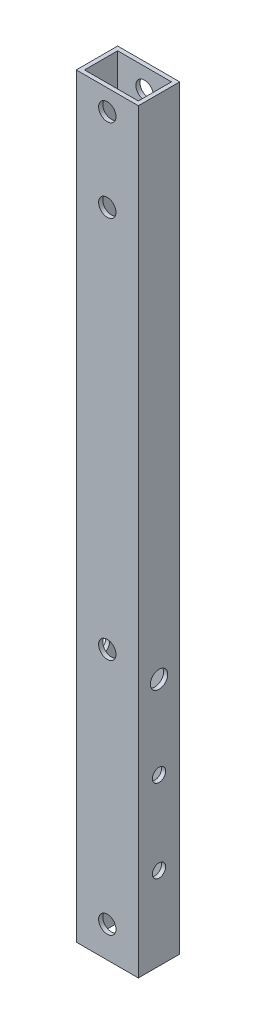
SolidWorks part; units mm, degrees
material "5052-H34"
ref_plane "正面" through (0, 0, 0) normal (0, 0, 1) x (1, 0, 0)
ref_plane "平面" through (0, 0, 0) normal (0, 1, 0) x (1, 0, 0)
ref_plane "右側面" through (0, 0, 0) normal (1, 0, 0) x (0, 0, -1)
sketch "ｽｹｯﾁ1" plane through (0, 0, 0) normal (0, 1, 0) x (1, 0, 0)
  line L1 (-7.5, 5) -> (7.5, 5)
  line L2 (-7.5, 5) -> (-7.5, -5)
  line L3 (-7.5, -5) -> (7.5, -5)
  line L4 (7.5, 5) -> (7.5, -5)
  line L5 (-7.5, 5) -> (7.5, -5) construction
  line L6 (-7.5, -5) -> (7.5, 5) construction
  point P0 (0, 0)
  dimension "D1" = 15
  dimension "D2" = 10
extrude "押し出し-薄板1" add sketch "ｽｹｯﾁ1" along normal blind 182.5 thin
sketch "ｽｹｯﾁ2" plane through (0, 0, 5) normal (0, 0, 1) x (1, 0, 0)
  line L0 (0, 182.5) -> (0, 0) construction
  line L1 (-7.5, 182.5) -> (7.5, 182.5) construction
  line L2 (0, 7.5) -> (-7.5, 7.5) construction
  line L4 (-7.5, 182.5) -> (-7.5, 0) construction
  line L5 (-7.5, 0) -> (7.5, 0) construction
  circle A2 centre (0, 7.5) radius 2.1
  circle A3 centre (0, 65) radius 2.1
  circle A4 centre (0, 157.5) radius 2.1
  circle A5 centre (0, 177.5) radius 2.1
  dimension "D1" = 4.2
  dimension "D3" = 57.5
  dimension "D2" = 7.5
  dimension "D4" = 5
  dimension "D5" = 20
extrude "ｶｯﾄ - 押し出し1" cut sketch "ｽｹｯﾁ2" against normal through all
sketch "ｽｹｯﾁ3" plane through (7.5, 0, 0) normal (1, 0, 0) x (0, 0, -1)
  line L0 (0, 0) -> (0, 20) construction
  line L1 (0, 20) -> (0, 60) construction
  line L3 (-5, 0) -> (5, 0) construction
  circle A0 centre (0, 20) radius 1.6
  circle A1 centre (0, 60) radius 2.1
  circle A4 centre (0, 40) radius 1.6
  dimension "D1" = 3.2
  dimension "D2" = 20
  dimension "D7" = 4.2
  dimension "D8" = 20
  dimension "D3" = 40
extrude "ｶｯﾄ - 押し出し2" cut sketch "ｽｹｯﾁ3" against normal through all
